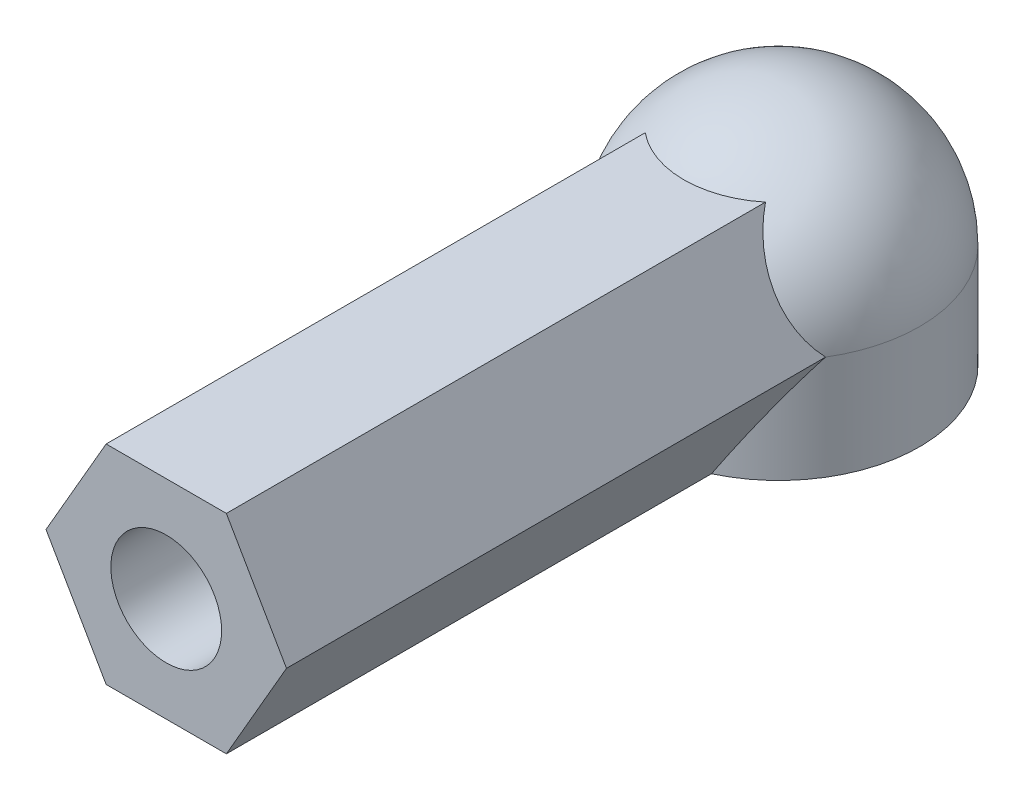
SolidWorks part; units mm, degrees
ref_plane "Front Plane" through (0, 0, 0) normal (0, 0, 1) x (1, 0, 0)
ref_plane "Top Plane" through (0, 0, 0) normal (0, 1, 0) x (1, 0, 0)
ref_plane "Right Plane" through (0, 0, 0) normal (1, 0, 0) x (0, 0, -1)
sketch "Sketch1" plane through (0, 0, 0) normal (0, 0, 1) x (1, 0, 0)
  line L0 (2.875, 2.125) -> (2.875, 0)
  line L1 (2.875, 0) -> (0, 0)
  line L2 (0, 0) -> (0, 5)
  line L3 (0, 0) -> (0, 5) construction
  arc A0 (2.875, 2.125) -> (0, 5) centre (0, 2.125) ccw
  dimension "D1" = 5.75
  dimension "D2" = 5
revolve "Revolve1" add sketch "Sketch1" angle 360 about L3
sketch "Sketch2" plane through (0, 0, 0) normal (0, 0, 1) x (1, 0, 0)
  line L0 (2.875, 2.125) -> (-2.875, 2.125) construction
  line L1 (-1.2269, 0) -> (1.2269, 0)
  line L2 (1.2269, 0) -> (2.4537, 2.125)
  line L3 (2.4537, 2.125) -> (1.2269, 4.25)
  line L4 (1.2269, 4.25) -> (-1.2269, 4.25)
  line L5 (-1.2269, 4.25) -> (-2.4537, 2.125)
  line L6 (-2.4537, 2.125) -> (-1.2269, 0)
  circle A0 centre (0, 2.125) radius 2.125 construction
  dimension "D1" = 4.25
extrude "Boss-Extrude1" add sketch "Sketch2" along normal blind 12.5
hole_wizard "#4-40 Tapped Hole1" positions "Sketch4" profile "Sketch3" tap size "#4-40" standard "ANSI Inch"
sketch "Sketch4" plane through (0, 0, 12.5) normal (0, 0, 1) x (1, 0, 0)
  line L0 (0, 0) -> (0, 2.125) construction
  line L1 (-1.2269, 0) -> (1.2269, 0) construction
  point P0 (0, 2.125)
sketch "Sketch3" plane through (0, 2.125, 12.5) normal (1, 0, 0) x (0, -1, 0)
  line L0 (0, 0) -> (0, 12.6792)
  line L1 (0, 12.6792) -> (1.1303, 12)
  line L2 (1.1303, 12) -> (1.1303, 0)
  line L5 (1.1303, 0) -> (0, 0)
  line L10 (0, 12.6792) -> (-1.1303, 12) construction
  line L11 (0, -6.35) -> (0, 107.95) construction
  dimension "Tap Drill Dia." = 2.2606
  dimension "Tap Drill Depth" = 12
  dimension "Drill Angle" = 118
cosmetic thread "Hole Thread1" parameters "D1"=5.69, "D2"=2.8448
sketch "Sketch5" plane through (0, 0, 0) normal (1, 0, 0) x (0, 0, -1)
  line L0 (-1.4983, 2.125) -> (2.875, 2.125) construction
  line L1 (2.1, 2.125) -> (2.1, 0)
  line L2 (-2.6001, 0) -> (2.875, 0) construction
  line L3 (2.1, 0) -> (0, 0)
  line L4 (0, 0) -> (0, 4.225)
  arc A0 (2.1, 2.125) -> (0, 4.225) centre (0, 2.125) ccw
  dimension "D1" = 4.2
revolve "Cut-Revolve1" cut sketch "Sketch5" angle 360 about L4
chamfer "Chamfer1" distance 0.375 angle 45 1 edges at (0, 0, -2.1)
